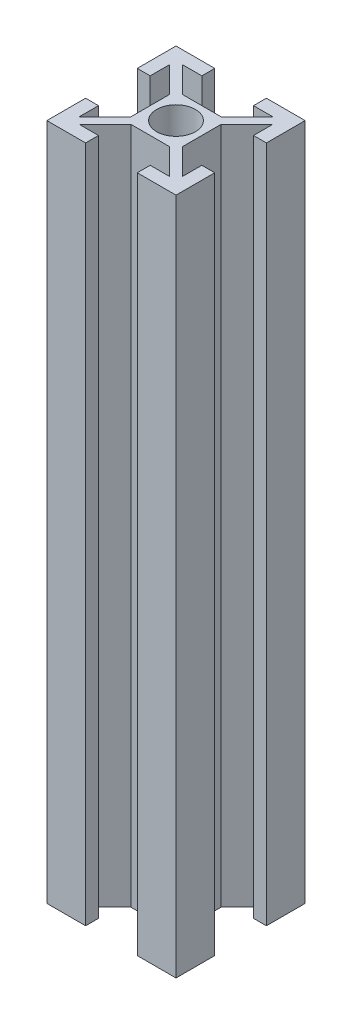
SolidWorks part; units mm, degrees
material "1060 Alloy"
ref_plane "Front Plane" through (0, 0, 0) normal (0, 0, 1) x (1, 0, 0)
ref_plane "Top Plane" through (0, 0, 0) normal (0, 1, 0) x (1, 0, 0)
ref_plane "Right Plane" through (0, 0, 0) normal (1, 0, 0) x (0, 0, -1)
sketch "2020 sketch" plane through (0, 0, 0) normal (0, 1, 0) x (1, 0, 0)
  line L0 (-4, 10) -> (-4, 8)
  line L1 (-10, 10) -> (-4, 10)
  line L2 (-10, 10) -> (-10, 4)
  line L3 (-10, -10) -> (-4, -10)
  line L4 (10, 10) -> (10, 4)
  line L5 (-10, 10) -> (10, -10) construction
  line L6 (-10, -10) -> (10, 10) construction
  line L7 (-4, 8) -> (-7, 8)
  line L8 (-7, 8) -> (-3, 4)
  line L9 (-3, 4) -> (3, 4)
  line L10 (3, 4) -> (7, 8)
  line L11 (7, 8) -> (4, 8)
  line L12 (4, 8) -> (4, 10)
  line L13 (4, 3) -> (4, -3)
  line L14 (8, 7) -> (4, 3)
  line L15 (8, 4) -> (8, 7)
  line L16 (10, 4) -> (8, 4)
  line L17 (8, -4) -> (10, -4)
  line L18 (8, -7) -> (8, -4)
  line L19 (4, -3) -> (8, -7)
  line L20 (3, -4) -> (-3, -4)
  line L21 (7, -8) -> (3, -4)
  line L22 (4, -8) -> (7, -8)
  line L23 (4, -10) -> (4, -8)
  line L24 (-4, -8) -> (-4, -10)
  line L25 (-7, -8) -> (-4, -8)
  line L26 (-3, -4) -> (-7, -8)
  line L27 (-4, -3) -> (-4, 3)
  line L28 (-8, -7) -> (-4, -3)
  line L29 (-8, -4) -> (-8, -7)
  line L30 (-10, -4) -> (-8, -4)
  line L31 (-8, 4) -> (-10, 4)
  line L32 (-8, 7) -> (-8, 4)
  line L33 (-4, 3) -> (-8, 7)
  line L34 (-10, -4) -> (-10, -10)
  line L35 (10, -4) -> (10, -10)
  line L36 (4, 10) -> (10, 10)
  line L37 (4, -10) -> (10, -10)
  circle A0 centre (0, 0) radius 3
  point P0 (0, 0)
  point P14 (4, 9)
  point P42 (0, 0)
  dimension "D9" = 6
  dimension "D1" = 20
  dimension "D2" = 20
  dimension "D3" = 8
  dimension "D4" = 6
  dimension "D5" = 6
  dimension "D6" = 2
  dimension "D7" = 4
  dimension "D8" = 4
extrude "Boss-Extrude1" add sketch "2020 sketch" along normal blind 105 contours A0 | L28 L27 L33 L32 L31 L2 L1 L0 L7 L8 L9 L10 L11 L12 L36 L4 L16 L15 L14 L13 L19 L18 L17 L35 L37 L23 L22 L21 L20 L26 L25 L24 L3 L34 L30 L29
